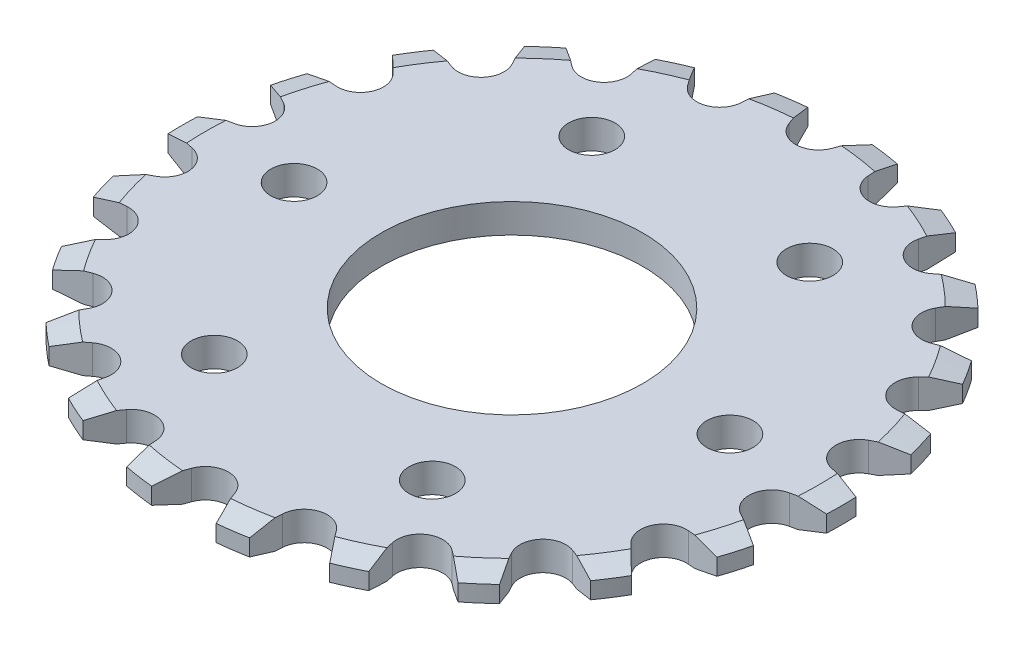
SolidWorks part; units mm, degrees
ref_plane "Front Plane" through (0, 0, 0) normal (0, 0, 1) x (1, 0, 0)
ref_plane "Top Plane" through (0, 0, 0) normal (0, 1, 0) x (1, 0, 0)
ref_plane "Right Plane" through (0, 0, 0) normal (1, 0, 0) x (0, 0, -1)
sketch "Sketch1" plane through (0, 0, 0) normal (0, 1, 0) x (1, 0, 0)
  circle A0 centre (0, 0) radius 36.0172
  circle A1 centre (0, 0) radius 14.2812
  dimension "D1" = 72.0344
  dimension "D2" = 28.5623
extrude "Boss-Extrude1" add sketch "Sketch1" along normal blind 3.175
sketch "Sketch2" plane through (0, 3.175, 0) normal (0, 1, 0) x (1, 0, 0)
  circle A0 centre (0, 0) radius 23.8125 construction
  circle A1 centre (-23.8125, 0) radius 2.54
  circle A2 centre (-11.9063, 20.6222) radius 2.54
  circle A3 centre (11.9062, 20.6222) radius 2.54
  circle A4 centre (23.8125, 0) radius 2.54
  circle A5 centre (11.9063, -20.6222) radius 2.54
  circle A6 centre (-11.9062, -20.6222) radius 2.54
  point P18 (0, 0)
  dimension "D1" = 47.625
  dimension "D2" = 5.08
  dimension "D3" = 6
extrude "Cut-Extrude1" cut sketch "Sketch2" against normal through all
chamfer "Chamfer1" distance 2.54 angle 15 2 edges at (0, 0, 36.0172) (0, 3.175, 36.0172)
sketch "Sketch3" plane through (0, 3.175, 0) normal (0, 1, 0) x (1, 0, 0)
  line L0 (0, 36.0172) -> (0, -36.0172) construction
  line L1 (2.363, 32.6426) -> (3.5282, 35.844)
  line L2 (-2.363, 32.6426) -> (-3.5282, 35.844)
  line L3 (6.9292, 31.986) -> (6.7132, 35.386)
  line L4 (11.4637, 30.6546) -> (13.4837, 33.398)
  line L5 (15.6601, 28.7382) -> (16.4106, 32.0613)
  line L6 (19.6357, 26.1832) -> (22.3468, 28.2464)
  line L7 (23.1222, 23.1621) -> (24.7786, 26.1392)
  line L8 (26.217, 19.5905) -> (29.3995, 20.8064)
  line L9 (28.7111, 15.7096) -> (31.1392, 18.0995)
  line L10 (30.6743, 11.4108) -> (34.0705, 11.6808)
  line L11 (31.974, 6.9844) -> (34.977, 8.5934)
  line L12 (32.6466, 2.3066) -> (35.9812, 1.6089)
  line L13 (32.6466, -2.3066) -> (35.9812, -1.6089)
  line L14 (31.974, -6.9844) -> (34.977, -8.5934)
  line L15 (30.6743, -11.4108) -> (34.0705, -11.6808)
  line L16 (28.7111, -15.7096) -> (31.1392, -18.0995)
  line L17 (26.217, -19.5905) -> (29.3995, -20.8064)
  line L18 (23.1222, -23.1621) -> (24.7786, -26.1392)
  line L19 (19.6357, -26.1832) -> (22.3468, -28.2464)
  line L20 (15.6601, -28.7382) -> (16.4106, -32.0613)
  line L21 (11.4637, -30.6546) -> (13.4837, -33.398)
  line L22 (6.9292, -31.986) -> (6.7132, -35.386)
  line L23 (2.363, -32.6426) -> (3.5282, -35.844)
  line L24 (-2.363, -32.6426) -> (-3.5282, -35.844)
  line L25 (-6.9292, -31.986) -> (-6.7132, -35.386)
  line L26 (-11.4637, -30.6546) -> (-13.4837, -33.398)
  line L27 (-15.6601, -28.7382) -> (-16.4106, -32.0613)
  line L28 (-19.6357, -26.1832) -> (-22.3468, -28.2464)
  line L29 (-23.1222, -23.1621) -> (-24.7786, -26.1392)
  line L30 (-26.217, -19.5905) -> (-29.3995, -20.8064)
  line L31 (-28.7111, -15.7096) -> (-31.1392, -18.0995)
  line L32 (-30.6743, -11.4108) -> (-34.0705, -11.6808)
  line L33 (-31.974, -6.9844) -> (-34.977, -8.5934)
  line L34 (-32.6466, -2.3066) -> (-35.9812, -1.6089)
  line L35 (-32.6466, 2.3066) -> (-35.9812, 1.6089)
  line L36 (-31.974, 6.9844) -> (-34.977, 8.5934)
  line L37 (-30.6743, 11.4108) -> (-34.0705, 11.6808)
  line L38 (-28.7111, 15.7096) -> (-31.1392, 18.0995)
  line L39 (-26.217, 19.5905) -> (-29.3995, 20.8064)
  line L40 (-23.1222, 23.1621) -> (-24.7786, 26.1392)
  line L41 (-19.6357, 26.1832) -> (-22.3468, 28.2464)
  line L42 (-15.6601, 28.7382) -> (-16.4106, 32.0613)
  line L43 (-11.4637, 30.6546) -> (-13.4837, 33.398)
  line L44 (-6.9292, 31.986) -> (-6.7132, 35.386)
  circle A0 centre (0, 0) radius 33.5026 construction
  circle A1 centre (0, 0) radius 36.0172 construction
  arc A2 (-2.363, 32.6426) -> (2.363, 32.6426) centre (0, 33.5026) ccw
  arc A3 (3.5282, 35.844) -> (-3.5282, 35.844) centre (0, 0) ccw
  arc A4 (6.9292, 31.986) -> (11.4637, 30.6546) centre (9.4388, 32.1455) ccw
  arc A5 (13.4837, 33.398) -> (6.7132, 35.386) centre (0, 0) ccw
  arc A6 (15.6601, 28.7382) -> (19.6357, 26.1832) centre (18.1129, 28.1842) ccw
  arc A7 (22.3468, 28.2464) -> (16.4106, 32.0613) centre (0, 0) ccw
  arc A8 (23.1222, 23.1621) -> (26.217, 19.5905) centre (25.3196, 21.9395) ccw
  arc A9 (29.3995, 20.8064) -> (24.7786, 26.1392) centre (0, 0) ccw
  arc A10 (28.7111, 15.7096) -> (30.6743, 11.4108) centre (30.475, 13.9175) ccw
  arc A11 (34.0705, 11.6808) -> (31.1392, 18.0995) centre (0, 0) ccw
  arc A12 (31.974, 6.9844) -> (32.6466, 2.3066) centre (33.1616, 4.7679) ccw
  arc A13 (35.9812, 1.6089) -> (34.977, 8.5934) centre (0, 0) ccw
  arc A14 (32.6466, -2.3066) -> (31.974, -6.9844) centre (33.1616, -4.7679) ccw
  arc A15 (34.977, -8.5934) -> (35.9812, -1.6089) centre (0, 0) ccw
  arc A16 (30.6743, -11.4108) -> (28.7111, -15.7096) centre (30.475, -13.9175) ccw
  arc A17 (31.1392, -18.0995) -> (34.0705, -11.6808) centre (0, 0) ccw
  arc A18 (26.217, -19.5905) -> (23.1222, -23.1621) centre (25.3196, -21.9395) ccw
  arc A19 (24.7786, -26.1392) -> (29.3995, -20.8064) centre (0, 0) ccw
  arc A20 (19.6357, -26.1832) -> (15.6601, -28.7382) centre (18.1129, -28.1842) ccw
  arc A21 (16.4106, -32.0613) -> (22.3468, -28.2464) centre (0, 0) ccw
  arc A22 (11.4637, -30.6546) -> (6.9292, -31.986) centre (9.4388, -32.1455) ccw
  arc A23 (6.7132, -35.386) -> (13.4837, -33.398) centre (0, 0) ccw
  arc A24 (2.363, -32.6426) -> (-2.363, -32.6426) centre (0, -33.5026) ccw
  arc A25 (-3.5282, -35.844) -> (3.5282, -35.844) centre (0, 0) ccw
  arc A26 (-6.9292, -31.986) -> (-11.4637, -30.6546) centre (-9.4388, -32.1455) ccw
  arc A27 (-13.4837, -33.398) -> (-6.7132, -35.386) centre (0, 0) ccw
  arc A28 (-15.6601, -28.7382) -> (-19.6357, -26.1832) centre (-18.1129, -28.1842) ccw
  arc A29 (-22.3468, -28.2464) -> (-16.4106, -32.0613) centre (0, 0) ccw
  arc A30 (-23.1222, -23.1621) -> (-26.217, -19.5905) centre (-25.3196, -21.9395) ccw
  arc A31 (-29.3995, -20.8064) -> (-24.7786, -26.1392) centre (0, 0) ccw
  arc A32 (-28.7111, -15.7096) -> (-30.6743, -11.4108) centre (-30.475, -13.9175) ccw
  arc A33 (-34.0705, -11.6808) -> (-31.1392, -18.0995) centre (0, 0) ccw
  arc A34 (-31.974, -6.9844) -> (-32.6466, -2.3066) centre (-33.1616, -4.7679) ccw
  arc A35 (-35.9812, -1.6089) -> (-34.977, -8.5934) centre (0, 0) ccw
  arc A36 (-32.6466, 2.3066) -> (-31.974, 6.9844) centre (-33.1616, 4.7679) ccw
  arc A37 (-34.977, 8.5934) -> (-35.9812, 1.6089) centre (0, 0) ccw
  arc A38 (-30.6743, 11.4108) -> (-28.7111, 15.7096) centre (-30.475, 13.9175) ccw
  arc A39 (-31.1392, 18.0995) -> (-34.0705, 11.6808) centre (0, 0) ccw
  arc A40 (-26.217, 19.5905) -> (-23.1222, 23.1621) centre (-25.3196, 21.9395) ccw
  arc A41 (-24.7786, 26.1392) -> (-29.3995, 20.8064) centre (0, 0) ccw
  arc A42 (-19.6357, 26.1832) -> (-15.6601, 28.7382) centre (-18.1129, 28.1842) ccw
  arc A43 (-16.4106, 32.0613) -> (-22.3468, 28.2464) centre (0, 0) ccw
  arc A44 (-11.4637, 30.6546) -> (-6.9292, 31.986) centre (-9.4388, 32.1455) ccw
  arc A45 (-6.7132, 35.386) -> (-13.4837, 33.398) centre (0, 0) ccw
  point P121 (0, 0)
  dimension "D1" = 67.0052
  dimension "D3" = 2.5146
  dimension "D2" = 20
  dimension "D4" = 22
extrude "Cut-Extrude2" cut sketch "Sketch3" against normal through all
